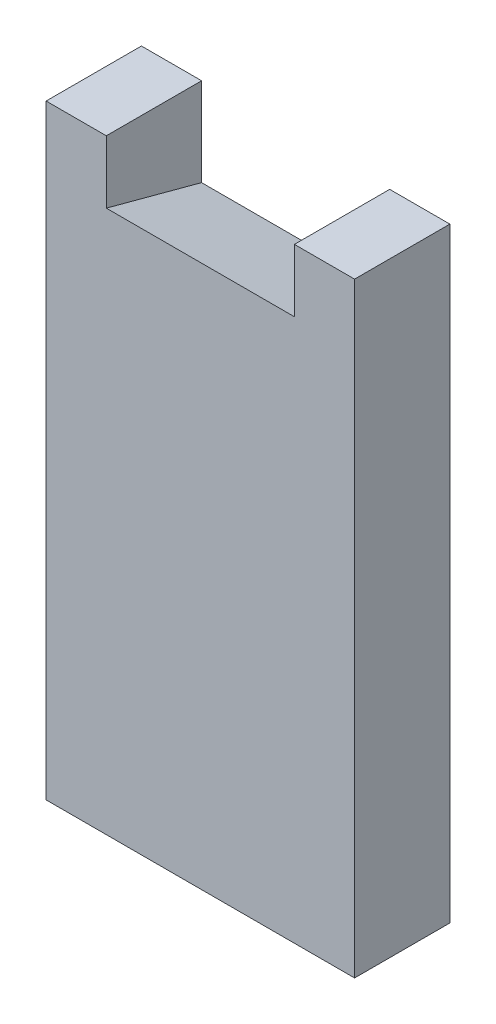
SolidWorks part; units mm, degrees
ref_plane "前视基准面" through (0, 0, 0) normal (0, 0, 1) x (1, 0, 0)
ref_plane "上视基准面" through (0, 0, 0) normal (0, 1, 0) x (1, 0, 0)
ref_plane "右视基准面" through (0, 0, 0) normal (1, 0, 0) x (0, 0, -1)
sketch "草图1" plane through (0, 0, 0) normal (0, 0, 1) x (1, 0, 0)
  line L1 (0, 0) -> (24.6, 0)
  line L2 (0, 0) -> (0, -48.27)
  line L3 (0, -48.27) -> (24.6, -48.27)
  line L4 (24.6, 0) -> (24.6, -48.27)
  line L5 (4.8, 0) -> (19.8, 0)
  line L6 (4.8, 0) -> (4.8, -5)
  line L7 (4.8, -5) -> (19.8, -5)
  line L8 (19.8, 0) -> (19.8, -5)
  point P9 (12.3, 0)
  dimension "D1" = 5
  dimension "D2" = 24.6
  dimension "D3" = 15
  dimension "D4" = 43.27
extrude "凸台-拉伸1" add sketch "草图1" along normal blind 7.6 contours L1 L8 L7 L6 L2 L3 L4
draft "拔模5" type of draft neutral plane draft angle 15 faces to draft 1 face at (12.3, -5, 3.8) neutral plane through (0, 0, 7.6) neutral plane normal (0, 0, 1) reverse direction yes parameters "D1"=15
